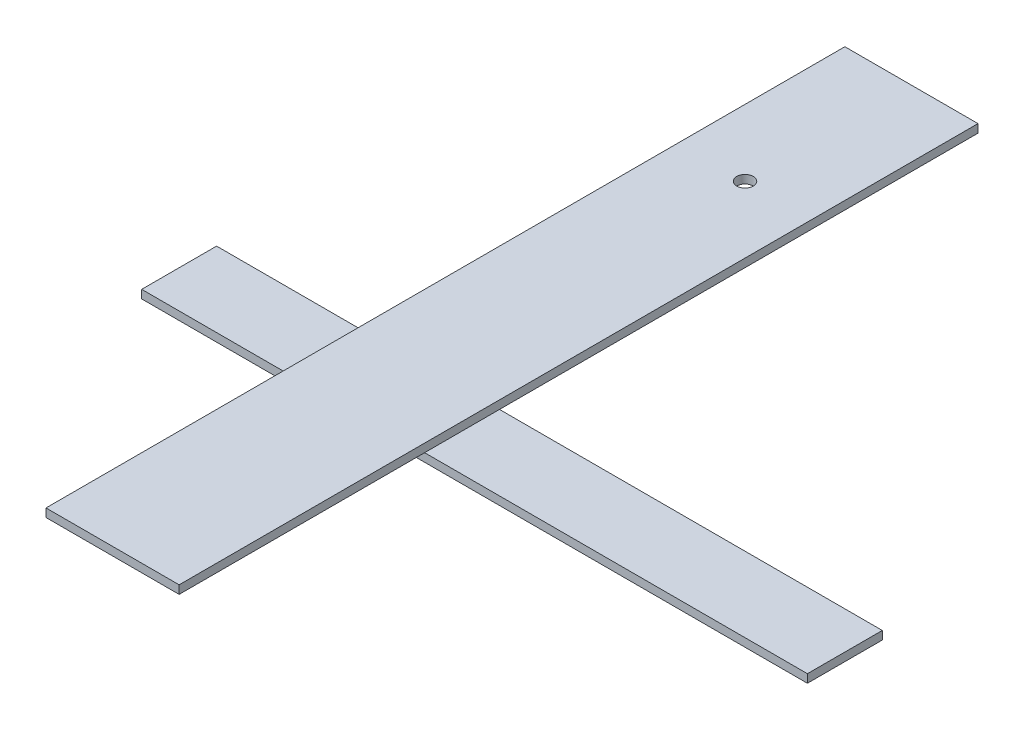
SolidWorks part; units mm, degrees
ref_plane "Front Plane" through (0, 0, 0) normal (0, 0, 1) x (1, 0, 0)
ref_plane "Top Plane" through (0, 0, 0) normal (0, 1, 0) x (1, 0, 0)
ref_plane "Right Plane" through (0, 0, 0) normal (1, 0, 0) x (0, 0, -1)
sketch "Sketch1" plane through (0, 0, 0) normal (1, 0, 0) x (0, 0, -1)
  line L1 (-28.575, 6.35) -> (28.575, 6.35)
  line L2 (-28.575, 6.35) -> (-28.575, 0)
  line L3 (-28.575, 0) -> (28.575, 0)
  line L4 (28.575, 6.35) -> (28.575, 0)
  dimension "D1" = 57.15
  dimension "D2" = 6.35
extrude "Boss-Extrude1" add sketch "Sketch1" along normal mid plane 508
sketch "Sketch2" plane through (0, 0, 0) normal (0, 0, 1) x (1, 0, 0)
  line L1 (-50.8, 101.6) -> (50.8, 101.6)
  line L2 (-50.8, 101.6) -> (-50.8, 95.25)
  line L3 (-50.8, 95.25) -> (50.8, 95.25)
  line L4 (50.8, 101.6) -> (50.8, 95.25)
  line L5 (254, 0) -> (-254, 0) construction
  point P4 (0, 95.25)
  dimension "D1" = 101.6
  dimension "D2" = 6.35
  dimension "D3" = 101.6
extrude "Boss-Extrude2" add sketch "Sketch2" along normal mid plane 609.6 separate body
sketch "Sketch3" plane through (0, 101.6, 0) normal (0, 1, 0) x (1, 0, 0)
  line L0 (0, 0) -> (0, 177.8) construction
  circle A0 centre (0, 177.8) radius 6.35
  dimension "D1" = 12.7
  dimension "D2" = 177.8
extrude "Cut-Extrude1" cut sketch "Sketch3" against normal up to next (6.35 mm away)
